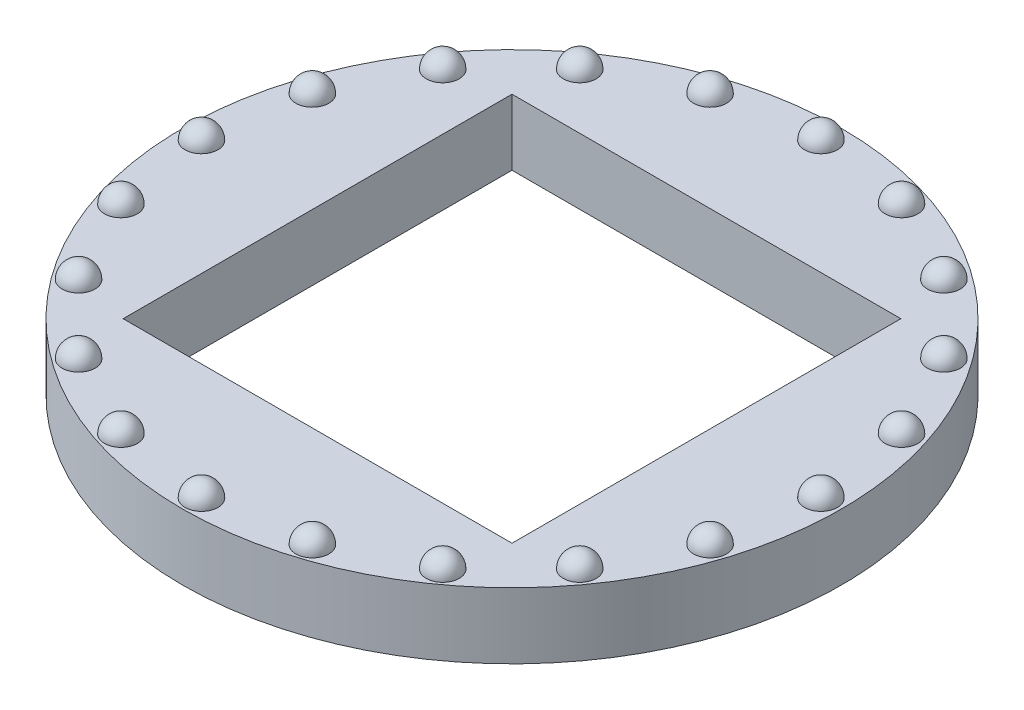
SolidWorks part; units mm, degrees
ref_plane "Front Plane" through (0, 0, 0) normal (0, 0, 1) x (1, 0, 0)
ref_plane "Top Plane" through (0, 0, 0) normal (0, 1, 0) x (1, 0, 0)
ref_plane "Right Plane" through (0, 0, 0) normal (1, 0, 0) x (0, 0, -1)
sketch "Sketch1" plane through (0, 0, 0) normal (0, 1, 0) x (1, 0, 0)
  circle A0 centre (0, 0) radius 40
  dimension "D1" = 80
extrude "Boss-Extrude1" add sketch "Sketch1" along normal blind 8
sketch "Sketch2" plane through (0, 8, 0) normal (0, 1, 0) x (1, 0, 0)
  circle A1 centre (0, 0) radius 35 construction
  circle A2 centre (0, 0) radius 37.5 construction
  circle A3 centre (0, 37.5) radius 2
  dimension "D1" = 75
sketch "Sketch3" plane through (0, 0, 0) normal (1, 0, 0) x (0, 0, -1)
  line L0 (37.5, 8) -> (37.5, 10)
  line L1 (37.5, 8) -> (39.5, 8)
  arc A0 (37.5, 10) -> (39.5, 8) centre (37.5, 8) cw
  dimension "D1" = 2
revolve "Revolve1" add sketch "Sketch3" angle 360 about L0
pattern_circular "CirPattern1" count 20 over 360 about axis through (0, 0, 0.094) along (0, 1, 0) of "Revolve1"
sketch "Sketch4" plane through (0, 0, 0) normal (0, -1, 0) x (1, 0, 0)
  line L1 (-23.6, 23.6) -> (23.6, 23.6)
  line L2 (-23.6, 23.6) -> (-23.6, -23.6)
  line L3 (-23.6, -23.6) -> (23.6, -23.6)
  line L4 (23.6, 23.6) -> (23.6, -23.6)
  line L5 (-23.6, 23.6) -> (23.6, -23.6) construction
  line L6 (-23.6, -23.6) -> (23.6, 23.6) construction
  point P0 (0, 0)
  dimension "D1" = 47.2
  dimension "D2" = 47.2
extrude "Cut-Extrude1" cut sketch "Sketch4" against normal blind 10
